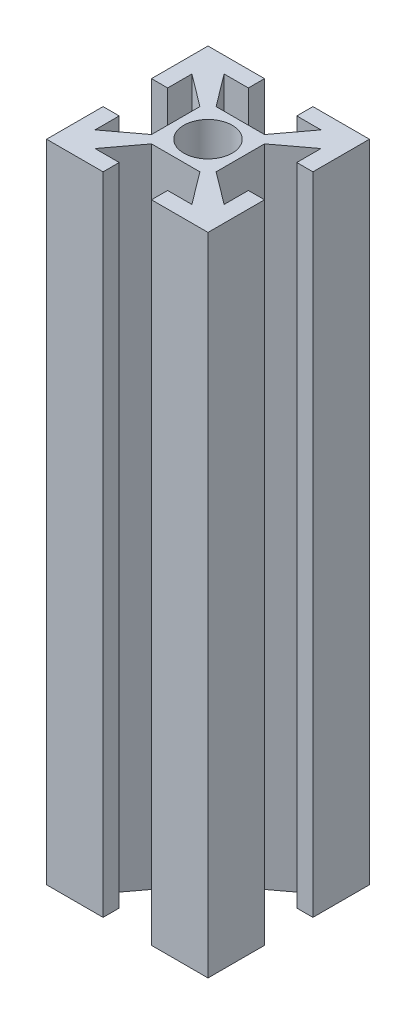
SolidWorks part; units mm, degrees
ref_plane "前基準面" through (0, 0, 0) normal (0, 0, 1) x (1, 0, 0)
ref_plane "上基準面" through (0, 0, 0) normal (0, 1, 0) x (1, 0, 0)
ref_plane "右基準面" through (0, 0, 0) normal (1, 0, 0) x (0, 0, -1)
sketch "草圖1" plane through (0, 0, 0) normal (0, 1, 0) x (1, 0, 0)
  line L0 (-10, 3) -> (-8, 3)
  line L1 (-10, 10) -> (-3, 10)
  line L2 (-10, 10) -> (-10, 3)
  line L3 (-10, -10) -> (-3, -10)
  line L4 (10, 10) -> (10, 3)
  line L5 (0, -10) -> (0, 10) construction
  line L6 (-10, 0) -> (10, 0) construction
  line L7 (3, 10) -> (3, 8)
  line L8 (-8, -3) -> (-10, -3)
  line L9 (-8, -3) -> (-8, -6)
  line L10 (-8, -6) -> (-4, -3)
  line L11 (-4, -3) -> (-4, 3)
  line L12 (-4, 3) -> (-8, 6)
  line L13 (-8, 6) -> (-8, 3)
  line L15 (-4, 3) -> (-4, -3)
  line L16 (-3, -4) -> (3, -4)
  line L17 (4, 3) -> (4, -3)
  line L18 (0, -4) -> (0, 3) construction
  line L19 (-4, 0) -> (4, 0) construction
  line L20 (-3, 8) -> (-3, 10)
  line L21 (-3, 8) -> (-6, 8)
  line L22 (-6, 8) -> (-3, 4)
  line L23 (3, 4) -> (6, 8)
  line L24 (6, 8) -> (3, 8)
  line L25 (10, -3) -> (8, -3)
  line L26 (8, 3) -> (10, 3)
  line L27 (8, 3) -> (8, 6)
  line L28 (8, 6) -> (4, 3)
  line L29 (4, -3) -> (8, -6)
  line L30 (8, -6) -> (8, -3)
  line L31 (-3, -10) -> (-3, -8)
  line L32 (3, -8) -> (3, -10)
  line L33 (3, -8) -> (6, -8)
  line L34 (6, -8) -> (3, -4)
  line L35 (-3, -4) -> (-6, -8)
  line L36 (-6, -8) -> (-3, -8)
  line L37 (-3, 4) -> (3, 4)
  line L38 (-10, -3) -> (-10, -10)
  line L39 (3, -10) -> (10, -10)
  line L40 (10, -3) -> (10, -10)
  line L41 (3, 10) -> (10, 10)
  circle A0 centre (0, 0) radius 3
  point P0 (0, 0)
  point P50 (0, 0)
  dimension "D3" = 6
  dimension "D2" = 20
  dimension "D6" = 6
  dimension "D7" = 2
  dimension "D8" = 12
  dimension "D10" = 126.87
  dimension "D11" = 4
extrude "填料-伸長1" add sketch "草圖1" along normal blind 80 contours L41 L7 L24 L23 L37 L22 L21 L20 L1 L2 L0 L13 L12 L11 L10 L9 L8 L38 L3 L31 L36 L35 L16 L34 L33 L32 L39 L40 L25 L30 L29 L17 L28 L27 L26 L4 A0
